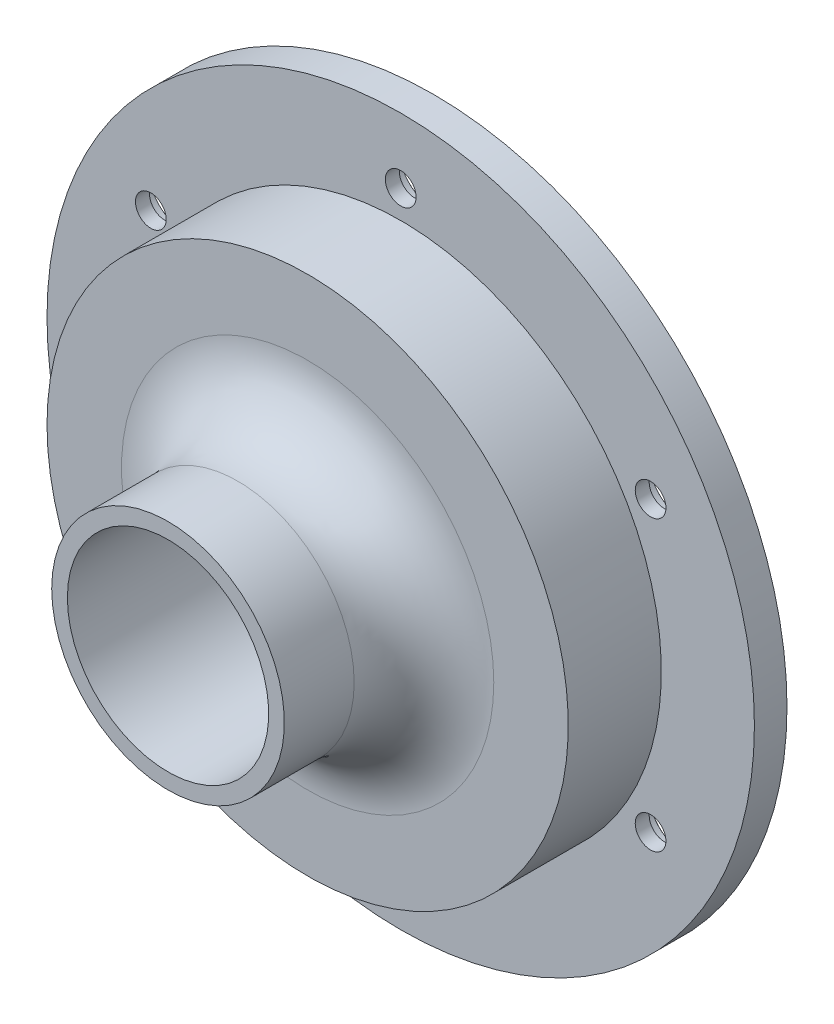
SolidWorks part; units mm, degrees
ref_plane "Front Plane" through (0, 0, 0) normal (0, 0, 1) x (1, 0, 0)
ref_plane "Top Plane" through (0, 0, 0) normal (0, 1, 0) x (1, 0, 0)
ref_plane "Right Plane" through (0, 0, 0) normal (1, 0, 0) x (0, 0, -1)
sketch "Sketch1" plane through (0, 0, 0) normal (0, 1, 0) x (1, 0, 0)
  line L0 (-76.0081, 0) -> (68.9919, 0) construction
  line L1 (-76.0081, 0) -> (-76.0081, -7)
  line L2 (-76.0081, -7) -> (-56.0081, -7)
  line L3 (-56.0081, -7) -> (-56.0081, -27)
  line L4 (-56.0081, -27) -> (-25, -27)
  line L5 (-25, -27) -> (-25, -57)
  line L6 (-25, -57) -> (-21.63, -57)
  line L7 (-21.63, -57) -> (-21.63, 0)
  line L8 (-21.63, 0) -> (-76.0081, 0)
  line L9 (0, 0) -> (0, -68.2269) construction
  dimension "D1" = 145
  dimension "D2" = 20
  dimension "D3" = 21.63
  dimension "D4" = 25
  dimension "D5" = 7
  dimension "D6" = 20
  dimension "D7" = 30
revolve "Revolve1" add sketch "Sketch1" angle 360 about L9
fillet "Fillet1" radius 15 1 edges at (-25, 0, 27)
hole_wizard "CBORE for M6 Hex Head Bolt1" positions "Sketch2" profile "Sketch3" counterbore size "M6" standard "ISO" end condition through all
sketch "Sketch2" plane through (0, 0, 0) normal (0, 0, -1) x (-1, 0, 0)
  point P0 (0, 62)
  dimension "D1" = 62
sketch "Sketch3" plane through (0, 62, 0) normal (1, 0, 0) x (0, 1, 0)
  line L0 (0, 0) -> (0, 57)
  line L1 (0, 57) -> (3.3, 57)
  line L3 (3.3, 57) -> (3.3, 4)
  line L4 (7.2735, 4) -> (3.3, 4)
  line L5 (7.2735, 4) -> (7.2735, 0.025)
  line L6 (7.2735, 0.025) -> (7.2985, 0)
  line L7 (7.2985, 0) -> (0, 0)
  line L8 (-7.2735, 0.025) -> (-7.2985, 0) construction
  line L11 (0, -6.35) -> (0, 107.95) construction
  dimension "Thru Hole Dia." = 6.6
  dimension "Thru Hole Depth" = 57
  dimension "C'Bore Dia." = 14.547
  dimension "C'Bore Depth" = 4
  dimension "Near C'Sink Dia." = 14.597
  dimension "Near C'Sink Angle" = 90
pattern_circular "CirPattern1" count 6 over 360 about axis through (0, 0, 0) along (0, 0, 1) of "CBORE for M6 Hex Head Bolt1"
